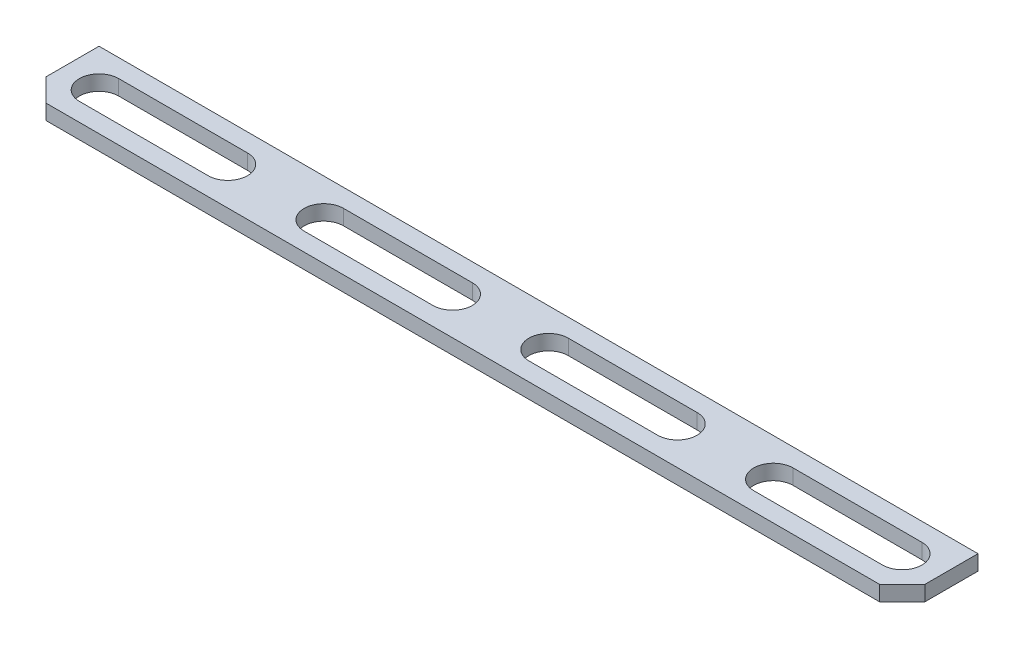
SolidWorks part; units mm, degrees
ref_plane "정면" through (0, 0, 0) normal (0, 0, 1) x (1, 0, 0)
ref_plane "윗면" through (0, 0, 0) normal (0, 1, 0) x (1, 0, 0)
ref_plane "우측면" through (0, 0, 0) normal (1, 0, 0) x (0, 0, -1)
sketch "스케치1" plane through (0, 0, 0) normal (0, 1, 0) x (1, 0, 0)
  line L1 (0, 0) -> (116, 0)
  line L2 (0, 0) -> (0, 10)
  line L3 (0, 10) -> (116, 10)
  line L4 (116, 0) -> (116, 10)
  dimension "D1" = 116
  dimension "D2" = 10
extrude "보스-돌출1" add sketch "스케치1" along normal blind 2
sketch "스케치2" plane through (0, 2, 0) normal (0, 1, 0) x (1, 0, 0)
  line L0 (5, 5) -> (22, 5) construction
  line L1 (5, 7.6) -> (22, 7.6)
  line L2 (5, 2.4) -> (22, 2.4)
  line L3 (34.6667, 5) -> (22, 5) construction
  line L4 (64.3333, 5) -> (51.6667, 5) construction
  line L5 (94, 5) -> (81.3333, 5) construction
  line L6 (34.6667, 5) -> (51.6667, 5) construction
  line L7 (34.6667, 7.6) -> (51.6667, 7.6)
  line L8 (34.6667, 2.4) -> (51.6667, 2.4)
  line L9 (64.3333, 5) -> (81.3333, 5) construction
  line L10 (64.3333, 7.6) -> (81.3333, 7.6)
  line L11 (64.3333, 2.4) -> (81.3333, 2.4)
  line L12 (94, 5) -> (111, 5) construction
  line L13 (94, 7.6) -> (111, 7.6)
  line L14 (94, 2.4) -> (111, 2.4)
  line L15 (5, 5) -> (0, 5) construction
  line L16 (0, 10) -> (0, 0) construction
  line L17 (116, 0) -> (116, 10) construction
  arc A0 (5, 7.6) -> (5, 2.4) centre (5, 5) ccw
  arc A1 (22, 2.4) -> (22, 7.6) centre (22, 5) ccw
  arc A4 (34.6667, 7.6) -> (34.6667, 2.4) centre (34.6667, 5) ccw
  arc A5 (51.6667, 2.4) -> (51.6667, 7.6) centre (51.6667, 5) ccw
  arc A6 (64.3333, 7.6) -> (64.3333, 2.4) centre (64.3333, 5) ccw
  arc A7 (81.3333, 2.4) -> (81.3333, 7.6) centre (81.3333, 5) ccw
  arc A8 (94, 7.6) -> (94, 2.4) centre (94, 5) ccw
  arc A9 (111, 2.4) -> (111, 7.6) centre (111, 5) ccw
  point P2 (13.5, 5)
  point P14 (43.1667, 5)
  point P21 (72.8333, 5)
  point P28 (102.5, 5)
  dimension "D4" = 2.6
  dimension "D1" = 17
  dimension "D2" = 5
  dimension "D3" = 5
extrude "컷-돌출1" cut sketch "스케치2" against normal blind 10
chamfer "모따기1" distance 3 angle 45 2 edges at (116, 1, 0) (0, 1, 0)
